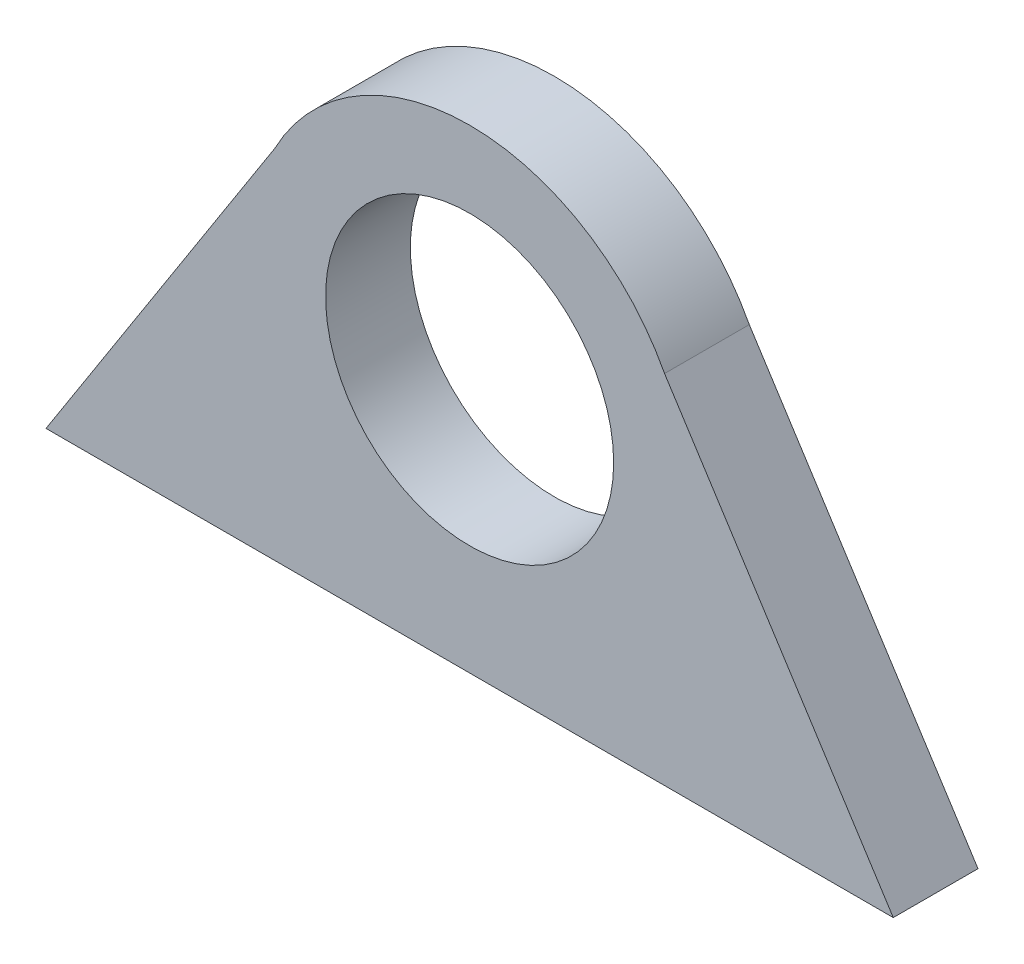
SolidWorks part; units mm, degrees
ref_plane "Front Plane" through (0, 0, 0) normal (0, 0, 1) x (1, 0, 0)
ref_plane "Top Plane" through (0, 0, 0) normal (0, 1, 0) x (1, 0, 0)
ref_plane "Right Plane" through (0, 0, 0) normal (1, 0, 0) x (0, 0, -1)
sketch "Sketch1" plane through (0, 0, 0) normal (0, 0, 1) x (1, 0, 0)
  line L0 (-25, -15) -> (25, -15)
  line L1 (-25, -15) -> (-11.5041, 6.0543)
  line L2 (25, -15) -> (11.5031, 6.0562)
  circle A0 centre (0, 0) radius 8.5
  arc A2 (11.5031, 6.0562) -> (-11.5041, 6.0543) centre (0, 0) ccw
  point P3 (-10.9296, 7.0388)
  point P4 (11.6698, 5.7284)
  point P7 (0, -15)
  point P8 (-11.5041, 6.0569)
  point P9 (11.5031, 6.0543)
  point P10 (-10.2919, 7.9421)
  point P11 (10.3068, 7.9421)
  point P14 (10.9926, 7.051)
  dimension "D1" = 17
  dimension "D2" = 15
  dimension "D4" = 26
  dimension "D3" = 50
extrude "Boss-Extrude1" add sketch "Sketch1" along normal blind 5
